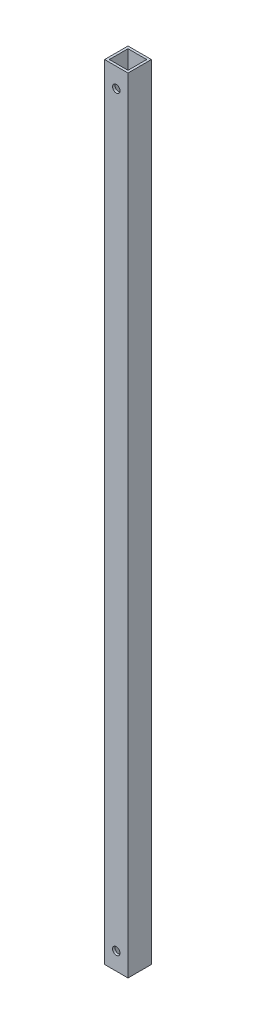
SolidWorks part; units mm, degrees
ref_plane "正面" through (0, 0, 0) normal (0, 0, 1) x (1, 0, 0)
ref_plane "平面" through (0, 0, 0) normal (0, 1, 0) x (1, 0, 0)
ref_plane "右側面" through (0, 0, 0) normal (1, 0, 0) x (0, 0, -1)
sketch "ｽｹｯﾁ1" plane through (0, 0, 0) normal (0, 0, 1) x (1, 0, 0)
  line L0 (0, 335) -> (10, 335)
  line L1 (10, 335) -> (10, 0)
  line L2 (10, 0) -> (0, 0)
  line L3 (0, 0) -> (0, 335)
  circle A2 centre (5, 326.6833) radius 1.6
  circle A3 centre (5, 7.5) radius 1.6
  dimension "D3" = 5
  dimension "D5" = 7.5
  dimension "D1" = 10
  dimension "D2" = 319.1833
  dimension "D6" = 5
  dimension "D7" = 0
  dimension "D4" = 335
extrude "ﾎﾞｽ - 押し出し1" add sketch "ｽｹｯﾁ1" along normal blind 10
sketch "ｽｹｯﾁ2" plane through (0, 0, 0) normal (0, -1, 0) x (1, 0, 0)
  line L8 (1, 1) -> (9, 1)
  line L9 (9, 1) -> (9, 9)
  line L10 (9, 9) -> (1, 9)
  line L11 (1, 9) -> (1, 1)
  line L12 (1, 1) -> (9, 1)
  line L13 (9, 1) -> (9, 9)
  line L14 (9, 9) -> (1, 9)
  line L15 (1, 9) -> (1, 1)
  dimension "D1" = 1
extrude "ｶｯﾄ - 押し出し1" cut sketch "ｽｹｯﾁ2" against normal blind 1000
